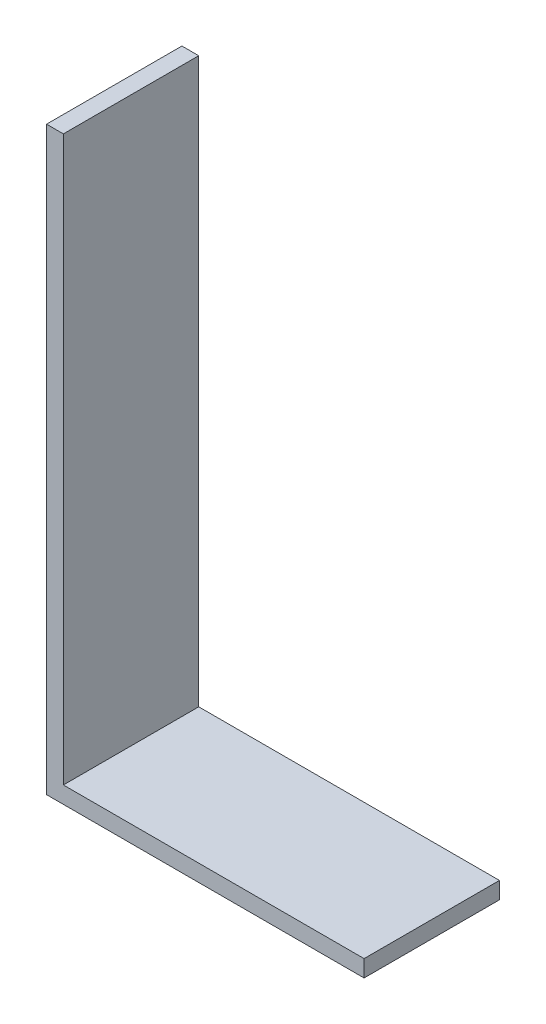
SolidWorks part; units mm, degrees
ref_plane "Alzado" through (0, 0, 0) normal (0, 0, 1) x (1, 0, 0)
ref_plane "Planta" through (0, 0, 0) normal (0, 1, 0) x (1, 0, 0)
ref_plane "Vista lateral" through (0, 0, 0) normal (1, 0, 0) x (0, 0, -1)
sketch "Croquis1" plane through (0, 0, 0) normal (0, 0, 1) x (1, 0, 0)
  line L0 (119.155, 6.31) -> (119.155, 0)
  line L1 (119.155, 0) -> (0, 0)
  line L2 (0, 0) -> (0, 217.9063)
  line L3 (0, 217.9063) -> (6.31, 217.9063)
  line L4 (6.31, 217.9063) -> (6.31, 6.31)
  line L5 (6.31, 6.31) -> (119.155, 6.31)
  point P7 (0, 0)
  point P10 (0, 0)
  point P11 (116.5959, 6.31)
  dimension "D1" = 217.9063
  dimension "D2" = 119.155
  dimension "D3" = 6.31
  dimension "D4" = 6.31
extrude "Saliente-Extruir1" add sketch "Croquis1" along normal blind 50.8
